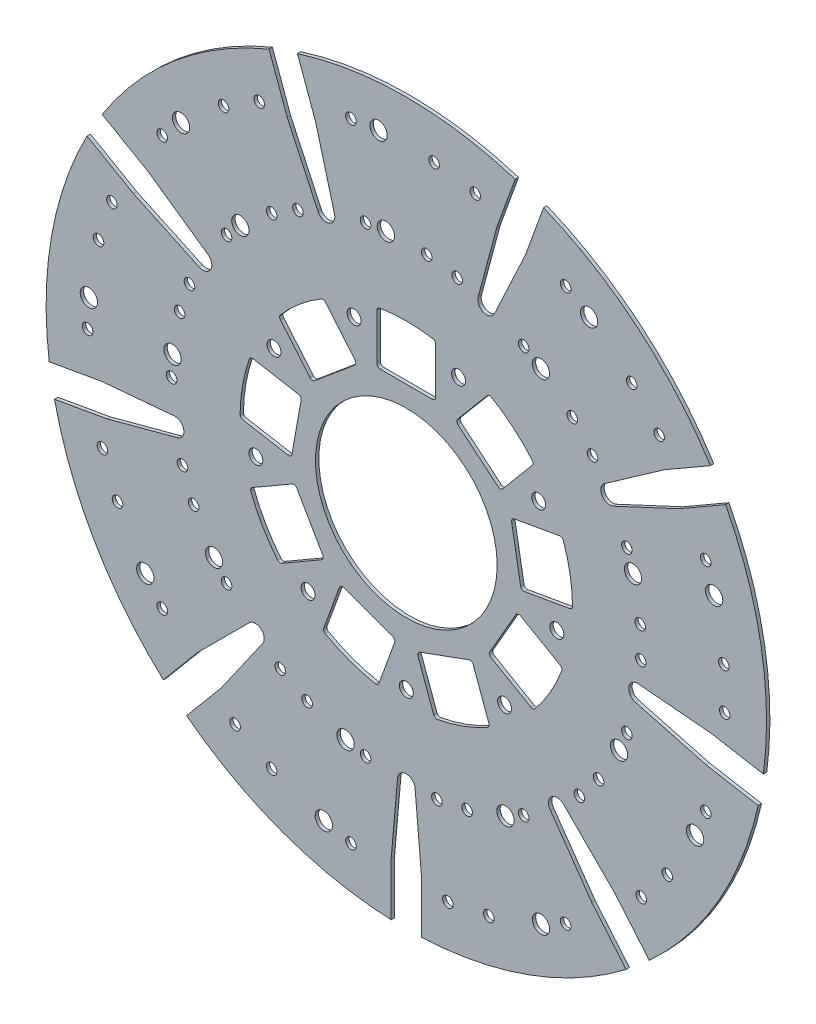
SolidWorks part; units mm, degrees
ref_plane "Plano frontal" through (0, 0, 0) normal (0, 0, 1) x (1, 0, 0)
ref_plane "Plano superior" through (0, 0, 0) normal (0, 1, 0) x (1, 0, 0)
ref_plane "Plano direito" through (0, 0, 0) normal (1, 0, 0) x (0, 0, -1)
sketch "Esboço1" plane through (0, 0, 0) normal (0, 0, 1) x (1, 0, 0)
  circle A0 centre (0, 0) radius 214.5
  circle A1 centre (0, 0) radius 54.1
  dimension "D1" = 108.2
  dimension "D2" = 429
extrude "Ressalto-extrusão1" add sketch "Esboço1" along normal blind 2
sketch "Esboço2" plane through (0, 0, 2) normal (0, 0, 1) x (1, 0, 0)
  line L0 (0, 0) -> (0, 214.5) construction
  line L8 (64.9255, 204.6957) -> (81.84, 198.5393)
  line L9 (64.9255, 204.6957) -> (53.9809, 174.6255)
  line L10 (81.84, 198.5393) -> (70.8864, 168.4446)
  line L11 (53.9809, 174.6255) -> (42.8337, 133.0238)
  line L12 (70.8864, 168.4446) -> (52.6956, 129.4343)
  line L13 (53.9809, 174.6255) -> (42.8337, 133.0238) construction
  line L14 (70.8864, 168.4446) -> (52.6956, 129.4343) construction
  line L22 (181.3117, 115.0727) -> (190.3117, 99.4842)
  line L23 (181.3117, 115.0727) -> (153.5989, 99.0727)
  line L24 (190.3117, 99.4842) -> (162.5763, 83.4712)
  line L25 (153.5989, 99.0727) -> (118.3186, 74.3691)
  line L26 (162.5763, 83.4712) -> (123.5659, 65.2803)
  line L27 (153.5989, 99.0727) -> (118.3186, 74.3691) construction
  line L28 (162.5763, 83.4712) -> (123.5659, 65.2803) construction
  line L36 (212.8601, -28.3941) -> (209.7345, -46.1207)
  line L37 (212.8601, -28.3941) -> (181.3463, -22.8374)
  line L38 (209.7345, -46.1207) -> (178.1949, -40.5594)
  line L39 (181.3463, -22.8374) -> (138.4409, -19.0837)
  line L40 (178.1949, -40.5594) -> (136.6184, -29.419)
  line L41 (181.3463, -22.8374) -> (138.4409, -19.0837) construction
  line L42 (178.1949, -40.5594) -> (136.6184, -29.419) construction
  line L50 (144.8089, -158.575) -> (131.0201, -170.1452)
  line L51 (144.8089, -158.575) -> (124.2397, -134.0616)
  line L52 (131.0201, -170.1452) -> (110.4341, -145.6118)
  line L53 (124.2397, -134.0616) -> (93.7851, -103.607)
  line L54 (110.4341, -145.6118) -> (85.7456, -110.3529)
  line L55 (124.2397, -134.0616) -> (93.7851, -103.607) construction
  line L56 (110.4341, -145.6118) -> (85.7456, -110.3529) construction
  line L64 (9, -214.5569) -> (-9, -214.5569)
  line L65 (9, -214.5569) -> (9, -182.5569)
  line L66 (-9, -214.5569) -> (-9, -182.5308)
  line L67 (9, -182.5569) -> (5.2463, -139.6515)
  line L68 (-9, -182.5308) -> (-5.2485, -139.6514)
  line L69 (9, -182.5569) -> (5.2463, -139.6515) construction
  line L70 (-9, -182.5308) -> (-5.2485, -139.6514) construction
  line L78 (-131.0201, -170.1452) -> (-144.8089, -158.575)
  line L79 (-131.0201, -170.1452) -> (-110.4509, -145.6318)
  line L80 (-144.8089, -158.575) -> (-124.2229, -134.0416)
  line L81 (-110.4509, -145.6318) -> (-85.7474, -110.3515)
  line L82 (-124.2229, -134.0416) -> (-93.7868, -103.6055)
  line L83 (-110.4509, -145.6318) -> (-85.7474, -110.3515) construction
  line L84 (-124.2229, -134.0416) -> (-93.7868, -103.6055) construction
  line L92 (-209.7345, -46.1207) -> (-212.8601, -28.3941)
  line L93 (-209.7345, -46.1207) -> (-178.2206, -40.5639)
  line L94 (-212.8601, -28.3941) -> (-181.3206, -22.8329)
  line L95 (-178.2206, -40.5639) -> (-136.6189, -29.4168)
  line L96 (-181.3206, -22.8329) -> (-138.4412, -19.0814)
  line L97 (-178.2206, -40.5639) -> (-136.6189, -29.4168) construction
  line L98 (-181.3206, -22.8329) -> (-138.4412, -19.0814) construction
  line L106 (-190.3117, 99.4842) -> (-181.3117, 115.0727)
  line L107 (-190.3117, 99.4842) -> (-162.5989, 83.4842)
  line L108 (-181.3117, 115.0727) -> (-153.5763, 99.0596)
  line L109 (-162.5989, 83.4842) -> (-123.5649, 65.2823)
  line L110 (-153.5763, 99.0596) -> (-118.3174, 74.3711)
  line L111 (-162.5989, 83.4842) -> (-123.5649, 65.2823) construction
  line L112 (-153.5763, 99.0596) -> (-118.3174, 74.3711) construction
  line L120 (-81.84, 198.5393) -> (-64.9255, 204.6957)
  line L121 (-81.84, 198.5393) -> (-70.8954, 168.4692)
  line L122 (-64.9255, 204.6957) -> (-53.972, 174.601)
  line L123 (-70.8954, 168.4692) -> (-52.6935, 129.4351)
  line L124 (-53.972, 174.601) -> (-42.8316, 133.0245)
  line L125 (-70.8954, 168.4692) -> (-52.6935, 129.4351) construction
  line L126 (-53.972, 174.601) -> (-42.8316, 133.0245) construction
  circle A0 centre (0, 0) radius 214.5 construction
  circle A1 centre (0, 0) radius 139.75 construction
  arc A3 (42.8337, 133.0238) -> (52.6956, 129.4343) centre (47.8212, 131.3842) ccw
  arc A5 (118.3186, 74.3691) -> (123.5659, 65.2803) centre (121.0853, 69.9073) ccw
  arc A7 (138.4409, -19.0837) -> (136.6184, -29.419) centre (137.6922, -24.28) ccw
  arc A9 (93.7851, -103.607) -> (85.7456, -110.3529) centre (89.8715, -107.1064) ccw
  arc A11 (5.2463, -139.6515) -> (-5.2485, -139.6514) centre (-0.0011, -139.8166) ccw
  arc A13 (-85.7474, -110.3515) -> (-93.7868, -103.6055) centre (-89.8732, -107.105) ccw
  arc A15 (-136.6189, -29.4168) -> (-138.4412, -19.0814) centre (-137.6926, -24.2778) ccw
  arc A17 (-123.5649, 65.2823) -> (-118.3174, 74.3711) centre (-121.0841, 69.9093) ccw
  arc A19 (-52.6935, 129.4351) -> (-42.8316, 133.0245) centre (-47.819, 131.385) ccw
  point P135 (0, 0)
  dimension "D2" = 279.5
extrude "Corte-extrusão1" cut sketch "Esboço2" against normal blind 2
sketch "Esboço3" plane through (0, 0, 2) normal (0, 0, 1) x (1, 0, 0)
  line L0 (0, 0) -> (0, 189.75) construction
  line L1 (0, 0) -> (-16.5378, 189.0279) construction
  line L2 (0, 0) -> (-32.9497, 186.8673) construction
  line L3 (0, 0) -> (16.5378, 189.0279) construction
  line L4 (0, 0) -> (41.0694, 185.2522) construction
  circle A0 centre (0, 0) radius 189.75 construction
  circle A1 centre (0, 0) radius 139.75 construction
  circle A2 centre (-32.9497, 186.8673) radius 3.15
  circle A3 centre (-24.2673, 137.6269) radius 3.15
  circle A4 centre (12.18, 139.2182) radius 3.15
  circle A5 centre (30.2474, 136.4374) radius 3.15
  circle A6 centre (41.0694, 185.2522) radius 3.15
  circle A7 centre (16.5378, 189.0279) radius 3.15
  circle A8 centre (-16.5378, 189.0279) radius 5.15
  circle A9 centre (-12.18, 139.2182) radius 5.15
  circle A10 centre (94.875, 164.3283) radius 3.15
  circle A11 centre (69.875, 121.0271) radius 3.15
  circle A12 centre (98.8182, 98.8182) radius 3.15
  circle A13 centre (110.8711, 85.0744) radius 3.15
  circle A14 centre (150.5388, 115.5125) radius 3.15
  circle A15 centre (134.1735, 134.1735) radius 3.15
  circle A16 centre (108.8361, 155.4341) radius 5.15
  circle A17 centre (80.1573, 114.4765) radius 5.15
  circle A18 centre (178.3067, 64.8983) radius 3.15
  circle A19 centre (131.322, 47.7973) radius 3.15
  circle A20 centre (139.2182, 12.18) radius 3.15
  circle A21 centre (139.617, -6.0958) radius 3.15
  circle A22 centre (189.5694, -8.2768) radius 3.15
  circle A23 centre (189.0279, 16.5378) radius 3.15
  circle A24 centre (183.2844, 49.1109) radius 5.15
  circle A25 centre (134.9881, 36.17) radius 5.15
  circle A26 centre (178.3067, -64.8983) radius 3.15
  circle A27 centre (131.322, -47.7973) radius 3.15
  circle A28 centre (114.4765, -80.1573) radius 3.15
  circle A29 centre (103.0345, -94.4137) radius 3.15
  circle A30 centre (139.8984, -128.1932) radius 3.15
  circle A31 centre (155.4341, -108.8361) radius 3.15
  circle A32 centre (171.9719, -80.1918) radius 5.15
  circle A33 centre (126.6565, -59.0609) radius 5.15
  circle A34 centre (94.875, -164.3283) radius 3.15
  circle A35 centre (69.875, -121.0271) radius 3.15
  circle A36 centre (36.17, -134.9881) radius 3.15
  circle A37 centre (18.241, -138.5544) radius 3.15
  circle A38 centre (24.7673, -188.1267) radius 3.15
  circle A39 centre (49.1109, -183.2844) radius 3.15
  circle A40 centre (80.1918, -171.9719) radius 5.15
  circle A41 centre (59.0609, -126.6565) radius 5.15
  circle A42 centre (-32.9497, -186.8673) radius 3.15
  circle A43 centre (-24.2673, -137.6269) radius 3.15
  circle A44 centre (-59.0609, -126.6565) radius 3.15
  circle A45 centre (-75.0876, -117.864) radius 3.15
  circle A46 centre (-101.9526, -160.0335) radius 3.15
  circle A47 centre (-80.1918, -171.9719) radius 3.15
  circle A48 centre (-49.1109, -183.2844) radius 5.15
  circle A49 centre (-36.17, -134.9881) radius 5.15
  circle A50 centre (-145.3569, -121.9689) radius 3.15
  circle A51 centre (-107.0547, -89.8296) radius 3.15
  circle A52 centre (-126.6565, -59.0609) radius 3.15
  circle A53 centre (-133.2819, -42.0236) radius 3.15
  circle A54 centre (-180.9678, -57.0589) radius 3.15
  circle A55 centre (-171.9719, -80.1918) radius 3.15
  circle A56 centre (-155.4341, -108.8361) radius 5.15
  circle A57 centre (-114.4765, -80.1573) radius 5.15
  circle A58 centre (-189.75, 0) radius 3.15
  circle A59 centre (-139.75, 0) radius 3.15
  circle A60 centre (-134.9881, 36.17) radius 3.15
  circle A61 centre (-129.1122, 53.48) radius 3.15
  circle A62 centre (-175.3061, 72.6142) radius 3.15
  circle A63 centre (-183.2844, 49.1109) radius 3.15
  circle A64 centre (-189.0279, 16.5378) radius 5.15
  circle A65 centre (-139.2182, 12.18) radius 5.15
  circle A66 centre (-145.3569, 121.9689) radius 3.15
  circle A67 centre (-107.0547, 89.8296) radius 3.15
  circle A68 centre (-80.1573, 114.4765) radius 3.15
  circle A69 centre (-64.5294, 123.9598) radius 3.15
  circle A70 centre (-87.6168, 168.3103) radius 3.15
  circle A71 centre (-108.8361, 155.4341) radius 3.15
  circle A72 centre (-134.1735, 134.1735) radius 5.15
  circle A73 centre (-98.8182, 98.8182) radius 5.15
  point P154 (0, 0)
  dimension "D1" = 379.5
  dimension "D2" = 279.5
  dimension "D7" = 6.3
  dimension "D8" = 10.3
  dimension "D3" = 5
  dimension "D4" = 5
  dimension "D5" = 5
  dimension "D6" = 7.5
extrude "Corte-extrusão3" cut sketch "Esboço3" against normal blind 2
sketch "Esboço4" plane through (0, 0, 2) normal (0, 0, 1) x (1, 0, 0)
  line L0 (-17.5, 66.4) -> (17.5, 66.4)
  line L1 (0, 99) -> (0, 66.4) construction
  line L2 (-17.5, 66.4) -> (-17.5, 97.441)
  line L3 (17.5, 66.4) -> (17.5, 97.441)
  line L4 (29.2753, 62.1141) -> (56.0869, 39.6166)
  line L5 (29.2753, 62.1141) -> (49.2281, 85.8929)
  line L6 (56.0869, 39.6166) -> (76.0397, 63.3954)
  line L7 (63.636, 75.8384) -> (42.6811, 50.8654) construction
  line L8 (62.3524, 28.7644) -> (68.4301, -5.7039)
  line L9 (62.3524, 28.7644) -> (92.9218, 34.1546)
  line L10 (68.4301, -5.7039) -> (98.9995, -0.3137)
  line L11 (97.496, 17.1912) -> (65.3912, 11.5302) construction
  line L12 (66.2541, -18.0446) -> (48.7541, -48.3554)
  line L13 (66.2541, -18.0446) -> (93.1364, -33.5651)
  line L14 (48.7541, -48.3554) -> (75.6364, -63.8759)
  line L15 (85.7365, -49.5) -> (57.5041, -33.2) construction
  line L16 (39.1548, -56.4102) -> (6.2655, -68.3809)
  line L17 (39.1548, -56.4102) -> (49.7714, -85.5792)
  line L18 (6.2655, -68.3809) -> (16.8822, -97.5499)
  line L19 (33.86, -93.0296) -> (22.7101, -62.3956) construction
  line L20 (-6.2655, -68.3809) -> (-39.1548, -56.4102)
  line L21 (-6.2655, -68.3809) -> (-16.8822, -97.5499)
  line L22 (-39.1548, -56.4102) -> (-49.7714, -85.5792)
  line L23 (-33.86, -93.0296) -> (-22.7101, -62.3956) construction
  line L24 (-48.7541, -48.3554) -> (-66.2541, -18.0446)
  line L25 (-48.7541, -48.3554) -> (-75.6364, -63.8759)
  line L26 (-66.2541, -18.0446) -> (-93.1364, -33.5651)
  line L27 (-85.7365, -49.5) -> (-57.5041, -33.2) construction
  line L28 (-68.4301, -5.7039) -> (-62.3524, 28.7644)
  line L29 (-68.4301, -5.7039) -> (-98.9995, -0.3137)
  line L30 (-62.3524, 28.7644) -> (-92.9218, 34.1546)
  line L31 (-97.496, 17.1912) -> (-65.3912, 11.5302) construction
  line L32 (-56.0869, 39.6166) -> (-29.2753, 62.1141)
  line L33 (-56.0869, 39.6166) -> (-76.0397, 63.3954)
  line L34 (-29.2753, 62.1141) -> (-49.2281, 85.8929)
  line L35 (-63.636, 75.8384) -> (-42.6811, 50.8654) construction
  arc A0 (49.2281, 85.8929) -> (76.0397, 63.3954) centre (0, 0) cw
  arc A1 (-17.5, 97.441) -> (17.5, 97.441) centre (0, 0) cw
  arc A2 (92.9218, 34.1546) -> (98.9995, -0.3137) centre (0, 0) cw
  arc A3 (93.1364, -33.5651) -> (75.6364, -63.8759) centre (0, 0) cw
  arc A4 (49.7714, -85.5792) -> (16.8822, -97.5499) centre (0, 0) cw
  arc A5 (-16.8822, -97.5499) -> (-49.7714, -85.5792) centre (0, 0) cw
  arc A6 (-75.6364, -63.8759) -> (-93.1364, -33.5651) centre (0, 0) cw
  arc A7 (-98.9995, -0.3137) -> (-92.9218, 34.1546) centre (0, 0) cw
  arc A8 (-76.0397, 63.3954) -> (-49.2281, 85.8929) centre (0, 0) cw
  point P58 (0, 0)
extrude "Corte-extrusão4" cut sketch "Esboço4" against normal blind 2
sketch "Esboço5" plane through (0, 0, 2) normal (0, 0, 1) x (1, 0, 0)
  line L0 (0, 0) -> (0, 91) construction
  circle A2 centre (31.1238, 85.512) radius 4.15
  circle A4 centre (78.8083, 45.5) radius 4.15
  circle A6 centre (89.6175, -15.802) radius 4.15
  circle A8 centre (58.4937, -69.71) radius 4.15
  circle A10 centre (0, -91) radius 4.15
  circle A12 centre (-58.4937, -69.71) radius 4.15
  circle A14 centre (-89.6175, -15.802) radius 4.15
  circle A16 centre (-78.8083, 45.5) radius 4.15
  circle A18 centre (-31.1238, 85.512) radius 4.15
  point P41 (0, 0)
extrude "Corte-extrusão5" cut sketch "Esboço5" against normal blind 2
fillet "Filete1" radius 2 2 edges at (-98.9995, -0.3137, 1) (-93.1364, -33.5651, 1)
fillet "Filete2" radius 2 2 edges at (-16.8822, -97.5499, 1) (-75.6364, -63.8759, 1)
fillet "Filete3" radius 2 5 edges at (16.8822, -97.5499, 1) (75.6364, -63.8759, 1) (56.0869, 39.6166, 1) (17.5, 66.4, 1) (-56.0869, 39.6166, 1)
fillet "Filete4" radius 2 27 edges at (-17.5, 66.4, 1) (-17.5, 97.441, 1) (-29.2753, 62.1141, 1) (-76.0397, 63.3954, 1) (-68.4301, -5.7039, 1) (-92.9218, 34.1546, 1) (-48.7541, -48.3554, 1) (-49.7714, -85.5792, 1) (-6.2655, -68.3809, 1) (-39.1548, -56.4102, 1) (6.2655, -68.3809, 1) (39.1548, -56.4102, 1) (49.7714, -85.5792, 1) (93.1364, -33.5651, 1) (48.7541, -48.3554, 1) (66.2541, -18.0446, 1) (98.9995, -0.3137, 1) (68.4301, -5.7039, 1) (92.9218, 34.1546, 1) (62.3524, 28.7644, 1) (76.0397, 63.3954, 1) (29.2753, 62.1141, 1) (49.2281, 85.8929, 1) (17.5, 97.441, 1) (-49.2281, 85.8929, 1) (-62.3524, 28.7644, 1) (-66.2541, -18.0446, 1)
